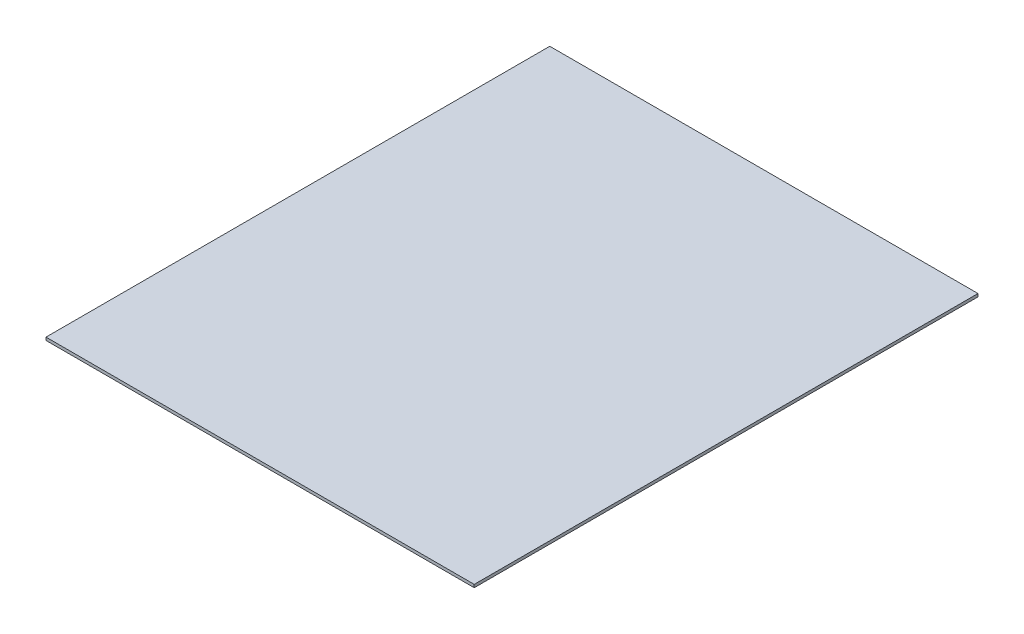
SolidWorks part; units mm, degrees
ref_plane "Front Plane" through (0, 0, 0) normal (0, 0, 1) x (1, 0, 0)
ref_plane "Top Plane" through (0, 0, 0) normal (0, 1, 0) x (1, 0, 0)
ref_plane "Right Plane" through (0, 0, 0) normal (1, 0, 0) x (0, 0, -1)
sketch "Sketch1" plane through (0, 0, 0) normal (0, 1, 0) x (1, 0, 0)
  line L0 (-111.5991, 133.5978) -> (-111.5991, -238.4022)
  line L1 (-111.5991, -238.4022) -> (180.4009, -238.4022)
  line L2 (180.4009, -238.4022) -> (180.4009, 133.5978)
  line L3 (180.4009, 133.5978) -> (-111.5991, 133.5978)
  dimension "D1" = 292
  dimension "D2" = 372
extrude "Boss-Extrude1" add sketch "Sketch1" along normal blind 2
sketch "Sketch2" plane through (0, 2, 0) normal (0, 1, 0) x (1, 0, 0)
  line L0 (180.4009, -238.4022) -> (180.4009, 133.5978) construction
  line L1 (-111.5991, -238.4022) -> (180.4009, -238.4022)
  line L2 (-111.5991, -238.4022) -> (-111.5991, -209.9022)
  line L3 (-111.5991, -209.9022) -> (180.4009, -209.9022)
  line L4 (180.4009, -238.4022) -> (180.4009, -209.9022)
  dimension "D1" = 28.5
extrude "Cut-Extrude1" cut sketch "Sketch2" against normal blind 2
